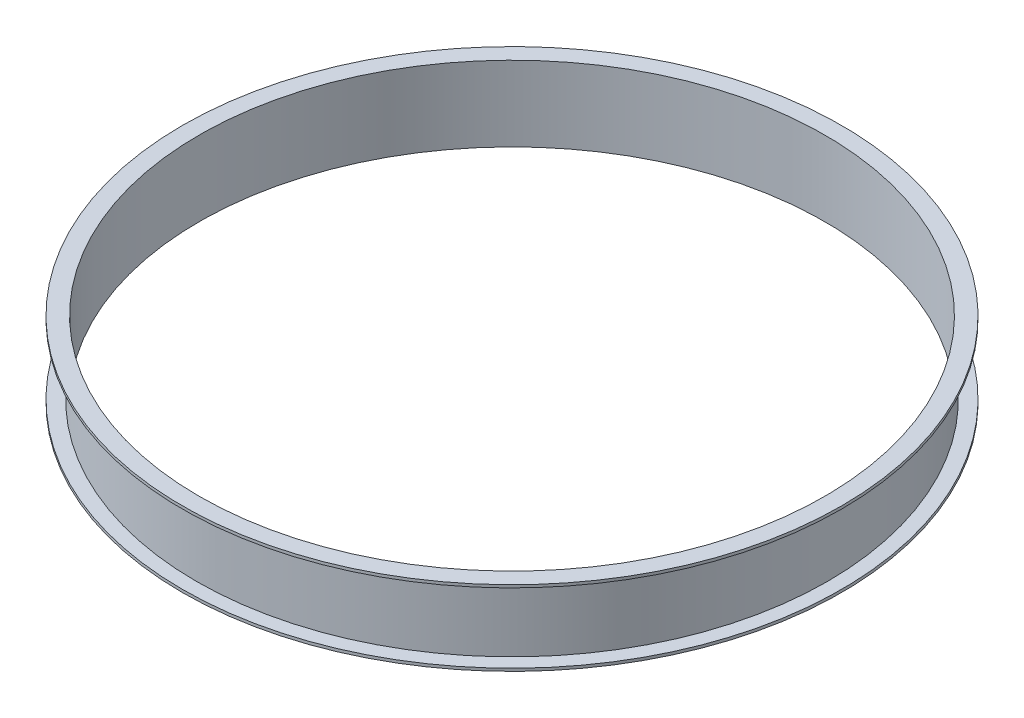
SolidWorks part; units mm, degrees
material "ASTM A36 Steel"
ref_plane "Front Plane" through (0, 0, 0) normal (0, 0, 1) x (1, 0, 0)
ref_plane "Top Plane" through (0, 0, 0) normal (0, 1, 0) x (1, 0, 0)
ref_plane "Right Plane" through (0, 0, 0) normal (1, 0, 0) x (0, 0, -1)
sketch "Sketch1" plane through (0, 0, 0) normal (0, 1, 0) x (1, 0, 0)
  circle A0 centre (0, 0) radius 237
  circle A1 centre (0, 0) radius 225
  dimension "D1" = 450
  dimension "D2" = 474
extrude "Boss-Extrude1" add sketch "Sketch1" along normal blind 2 contours A1
sketch "Sketch2" plane through (0, 2, 0) normal (0, 1, 0) x (1, 0, 0)
  circle A0 centre (0, 0) radius 225 construction
  circle A1 centre (0, 0) radius 225
extrude "Extrude-Thin1" add sketch "Sketch2" along normal blind 50 thin
sketch "Sketch3" plane through (0, 52, 0) normal (0, 1, 0) x (1, 0, 0)
  circle A0 centre (0, 0) radius 225 construction
  circle A1 centre (0, 0) radius 225
extrude "Extrude-Thin2" add sketch "Sketch3" along normal blind 2 thin
